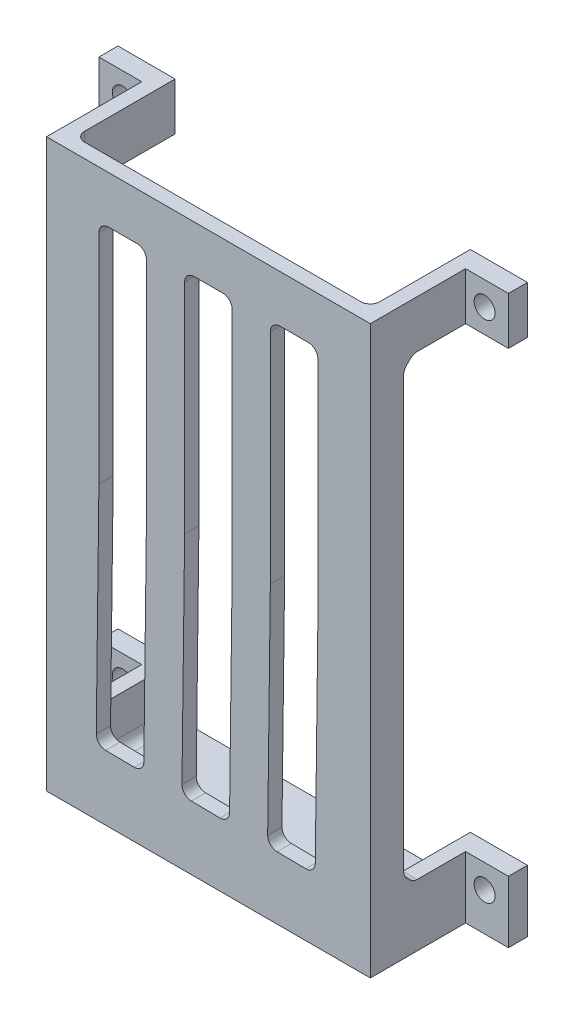
SolidWorks part; units mm, degrees
ref_plane "Front Plane" through (0, 0, 0) normal (0, 0, 1) x (1, 0, 0)
ref_plane "Top Plane" through (0, 0, 0) normal (0, 1, 0) x (1, 0, 0)
ref_plane "Right Plane" through (0, 0, 0) normal (1, 0, 0) x (0, 0, -1)
sketch "Sketch1" plane through (0, 0, 0) normal (0, 0, 1) x (1, 0, 0)
  line L4 (15.5, 48) -> (21.5, 48)
  line L5 (21.5, 48) -> (21.5, 53)
  line L6 (21.5, 53) -> (15.5, 53)
  line L7 (15.5, 53) -> (15.5, 48)
  line L8 (15.5, 48) -> (21.5, 48)
  line L9 (21.5, 48) -> (21.5, 53)
  line L10 (21.5, 53) -> (15.5, 53)
  line L11 (15.5, 53) -> (15.5, 48)
  line L12 (-21.5, 48) -> (-15.5, 48)
  line L13 (-15.5, 48) -> (-15.5, 53)
  line L14 (-15.5, 53) -> (-21.5, 53)
  line L15 (-21.5, 53) -> (-21.5, 48)
  line L16 (-21.5, 48) -> (-15.5, 48)
  line L17 (-15.5, 48) -> (-15.5, 53)
  line L18 (-15.5, 53) -> (-21.5, 53)
  line L19 (-21.5, 53) -> (-21.5, 48)
  line L20 (21.5, 0) -> (15.5, 0)
  line L21 (15.5, 0) -> (15.5, -5)
  line L22 (15.5, -5) -> (21.5, -5)
  line L23 (21.5, -5) -> (21.5, 0)
  line L24 (21.5, 0) -> (15.5, 0)
  line L25 (15.5, 0) -> (15.5, -5)
  line L26 (15.5, -5) -> (21.5, -5)
  line L27 (21.5, -5) -> (21.5, 0)
  line L28 (-15.5, 0) -> (-21.5, 0)
  line L29 (-21.5, 0) -> (-21.5, -5)
  line L30 (-21.5, -5) -> (-15.5, -5)
  line L31 (-15.5, -5) -> (-15.5, 0)
  line L32 (-15.5, 0) -> (-21.5, 0)
  line L33 (-21.5, 0) -> (-21.5, -5)
  line L34 (-21.5, -5) -> (-15.5, -5)
  line L35 (-15.5, -5) -> (-15.5, 0)
  circle A0 centre (-19, 50.5) radius 1.1
  circle A1 centre (19, 50.5) radius 1.1
  circle A2 centre (19, -2.5) radius 1.1
  circle A3 centre (-19, -2.5) radius 1.1
  dimension "D1" = 2.2
  dimension "D2" = 2.2
  dimension "D3" = 2.2
  dimension "D4" = 2.2
  dimension "D5" = 0
  dimension "D6" = 0
  dimension "D7" = 0
  dimension "D8" = 0
extrude "Boss-Extrude1" add sketch "Sketch1" along normal blind 2
sketch "Sketch2" plane through (0, 0, 2) normal (0, 0, 1) x (1, 0, 0)
  line L0 (15.5, 53) -> (17, 53)
  line L1 (15.5, 53) -> (21.5, 53) construction
  line L2 (17, 53) -> (17, 48)
  line L3 (15.5, 48) -> (21.5, 48) construction
  line L4 (17, 48) -> (15.5, 48)
  line L5 (15.5, 48) -> (15.5, 53)
  line L6 (15.5, 0) -> (15.5, -5)
  line L7 (21.5, 0) -> (15.5, 0) construction
  line L8 (21.5, 0) -> (15.5, 0) construction
  line L9 (15.5, -5) -> (17, -5)
  line L10 (21.5, -5) -> (15.5, -5) construction
  line L11 (17, -5) -> (17, 0)
  line L12 (17, 0) -> (15.5, 0)
  line L13 (0, 0) -> (0, 23) construction
  line L15 (-17, 0) -> (-15.5, 0)
  line L16 (-17, -5) -> (-17, 0)
  line L17 (-15.5, -5) -> (-17, -5)
  line L18 (-15.5, 0) -> (-15.5, -5)
  line L19 (-15.5, 48) -> (-15.5, 53)
  line L20 (-17, 48) -> (-15.5, 48)
  line L21 (-17, 53) -> (-17, 48)
  line L22 (-15.5, 53) -> (-17, 53)
  dimension "D1" = 1.5
  dimension "D2" = 1.5
extrude "Boss-Extrude2" add sketch "Sketch2" along normal blind 10
sketch "Sketch3" plane through (0, 0, 12) normal (0, 0, 1) x (1, 0, 0)
  line L0 (-17, 53) -> (17, 53)
  line L1 (17, 53) -> (17, -5)
  line L2 (17, -5) -> (-17, -5)
  line L3 (-17, -5) -> (-17, 53)
extrude "Boss-Extrude3" add sketch "Sketch3" against normal blind 1.5
sketch "Sketch4" plane through (0, -5, 0) normal (0, -1, 0) x (1, 0, 0)
  line L0 (-15.5, 0) -> (15.5, 0)
  line L12 (-17, 12) -> (-17, 2)
  line L13 (-17, 2) -> (-21.5, 2)
  line L14 (-21.5, 2) -> (-21.5, 0)
  line L15 (-21.5, 0) -> (-15.5, 0)
  line L16 (-15.5, 0) -> (-15.5, 10.5)
  line L17 (-15.5, 10.5) -> (15.5, 10.5)
  line L18 (15.5, 10.5) -> (15.5, 0)
  line L19 (15.5, 0) -> (21.5, 0)
  line L20 (21.5, 0) -> (21.5, 2)
  line L21 (21.5, 2) -> (17, 2)
  line L22 (17, 2) -> (17, 12)
  line L23 (17, 12) -> (-17, 12)
  line L24 (-17, 12) -> (-17, 2)
  line L25 (-17, 2) -> (-21.5, 2)
  line L26 (-21.5, 2) -> (-21.5, 0)
  line L27 (-21.5, 0) -> (-15.5, 0)
  line L28 (-15.5, 0) -> (-15.5, 10.5) construction
  line L29 (-15.5, 10.5) -> (15.5, 10.5) construction
  line L30 (15.5, 10.5) -> (15.5, 0) construction
  line L31 (15.5, 0) -> (21.5, 0)
  line L32 (21.5, 0) -> (21.5, 2)
  line L33 (21.5, 2) -> (17, 2)
  line L34 (17, 2) -> (17, 12)
  line L35 (17, 12) -> (-17, 12)
  dimension "D1" = 0
extrude "Boss-Extrude4" add sketch "Sketch4" along normal blind 1.5
chamfer "Chamfer1" distance 3 angle 45 4 edges at (-16.25, 0, 10.5) (-16.25, 48, 10.5) (16.25, 0, 10.5) (16.25, 48, 10.5)
sketch "Sketch5" plane through (0, 0, 10.5) normal (0, 0, -1) x (-1, 0, 0)
  line L0 (0, 74.4171) -> (0, -49.9332) construction
  line L1 (-17, 24) -> (29.3548, 24) construction
  line L2 (-17, 3) -> (-17, 45) construction
  line L3 (15.5, 49) -> (17, 49)
  line L4 (15.5, 45) -> (15.5, 48) construction
  line L5 (17, 48) -> (17, 45) construction
  line L6 (17, 49) -> (17, -1)
  line L7 (17, 45) -> (17, 3) construction
  line L8 (15.5, 49) -> (15.5, -1)
  line L9 (-15.5, 49) -> (-15.5, -1)
  line L10 (-17, 49) -> (-17, -1)
  line L11 (-15.5, 49) -> (-17, 49)
  line L12 (-15.5, -1) -> (-17, -1)
  line L13 (15.5, -1) -> (17, -1)
  point P22 (-15.5, 24)
  point P23 (15.5, 24)
  point P24 (17, 24)
  dimension "D1" = 50
extrude "Boss-Extrude5" add sketch "Sketch5" along normal blind 2
fillet "Fillet1" radius 1 12 edges at (-16.25, 48, 7.5) (16.25, 48, 7.5) (16.25, 47, 8.5) (-16.25, 0, 7.5) (-16.25, 1, 8.5) (16.25, 1, 8.5) (16.25, 0, 7.5) (15.5, 24, 10.5) (15.5, -5, 5.25) (-15.5, -5, 5.25) (-15.5, 24, 10.5) (0, -5, 10.5)
sketch "Sketch6" plane through (0, 0, 10.5) normal (0, 0, -1) x (-1, 0, 0)
  line L0 (0, 73.3874) -> (0, -16.506) construction
  line L1 (-17, 24) -> (17, 24.2071) construction
  line L2 (-17, 46.5858) -> (-17, 1.4142) construction
  line L3 (17, 1.4142) -> (17, 47) construction
  line L4 (-11.5, 48.0335) -> (-11.5, 24.0335)
  line L5 (-11.5, 48.0335) -> (-6.5, 48.0335)
  line L6 (-6.5, 48.0335) -> (-6.5, 24.064)
  line L7 (-2.5, 24.0883) -> (-2.5, 48.0335)
  line L8 (-2.5, 48.0335) -> (2.5, 48.0335)
  line L9 (2.5, 24.0883) -> (2.5, 48.0335)
  line L10 (6.5, 48.0335) -> (6.5, 24.064)
  line L11 (11.5, 48.0335) -> (6.5, 48.0335)
  line L12 (11.5, 48.0335) -> (11.5, 24.0335)
  line L13 (11.7907, 0.3155) -> (11.4983, 24.3137)
  line L14 (11.7907, 0.3155) -> (6.791, 0.2546)
  line L15 (6.791, 0.2546) -> (6.499, 24.2223)
  line L16 (2.4996, 24.1492) -> (2.7913, 0.2058)
  line L17 (-2.2083, 0.1449) -> (2.7913, 0.2058)
  line L18 (-2.5, 24.0883) -> (-2.2083, 0.1449)
  line L19 (-6.208, 0.0962) -> (-6.5, 24.064)
  line L20 (-11.2076, 0.0353) -> (-6.208, 0.0962)
  line L21 (-11.2076, 0.0353) -> (-11.5, 24.0335)
  point P17 (0, 48.0335)
  point P22 (0.2915, 0.1754)
  dimension "D1" = 5
  dimension "D2" = 5
  dimension "D3" = 4
  dimension "D4" = 24
extrude "Cut-Extrude1" cut sketch "Sketch6" against normal blind 2
fillet "Fillet2" radius 1 12 edges at (6.208, 0.0962, 11.25) (-2.7913, 0.2058, 11.25) (-11.7907, 0.3155, 11.25) (-6.791, 0.2546, 11.25) (2.2083, 0.1449, 11.25) (11.2076, 0.0353, 11.25) (-11.5, 48.0335, 11.25) (-6.5, 48.0335, 11.25) (-2.5, 48.0335, 11.25) (2.5, 48.0335, 11.25) (6.5, 48.0335, 11.25) (11.5, 48.0335, 11.25)
